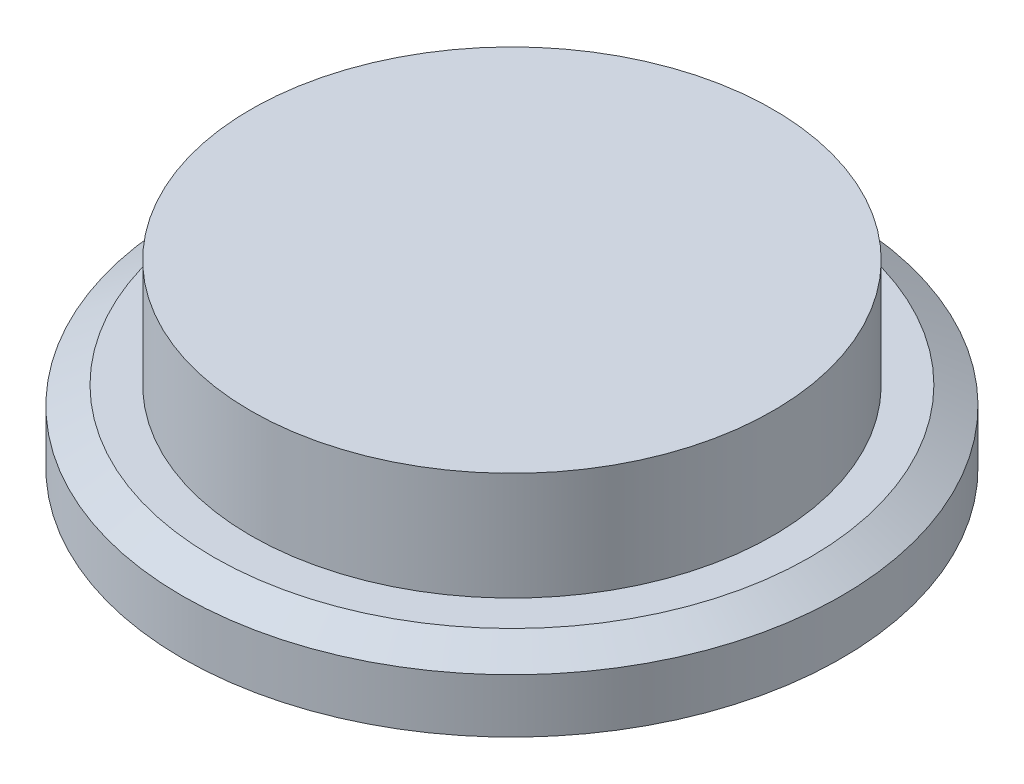
SolidWorks part; units mm, degrees
ref_plane "Front Plane" through (0, 0, 0) normal (0, 0, 1) x (1, 0, 0)
ref_plane "Top Plane" through (0, 0, 0) normal (0, 1, 0) x (1, 0, 0)
ref_plane "Right Plane" through (0, 0, 0) normal (1, 0, 0) x (0, 0, -1)
sketch "Sketch5" plane through (0, 0, 0) normal (0, 1, 0) x (1, 0, 0)
  circle A0 centre (0, 0) radius 6
  dimension "D1" = 12
extrude "Boss-Extrude3" add sketch "Sketch5" along normal blind 1
sketch "Sketch6" plane through (0, 1, 0) normal (0, 1, 0) x (1, 0, 0)
  circle A3 centre (0, 0) radius 9.15
  dimension "D1" = 18.3
extrude "Boss-Extrude4" add sketch "Sketch6" along normal blind 2
chamfer "Chamfer1" distance 0.5 angle 60 1 edges at (0, 3, 9.15)
sketch "Sketch7" plane through (0, 3, 0) normal (0, 1, 0) x (1, 0, 0)
  circle A0 centre (0, 0) radius 7.25
  dimension "D1" = 14.5
extrude "Boss-Extrude5" add sketch "Sketch7" along normal blind 3
